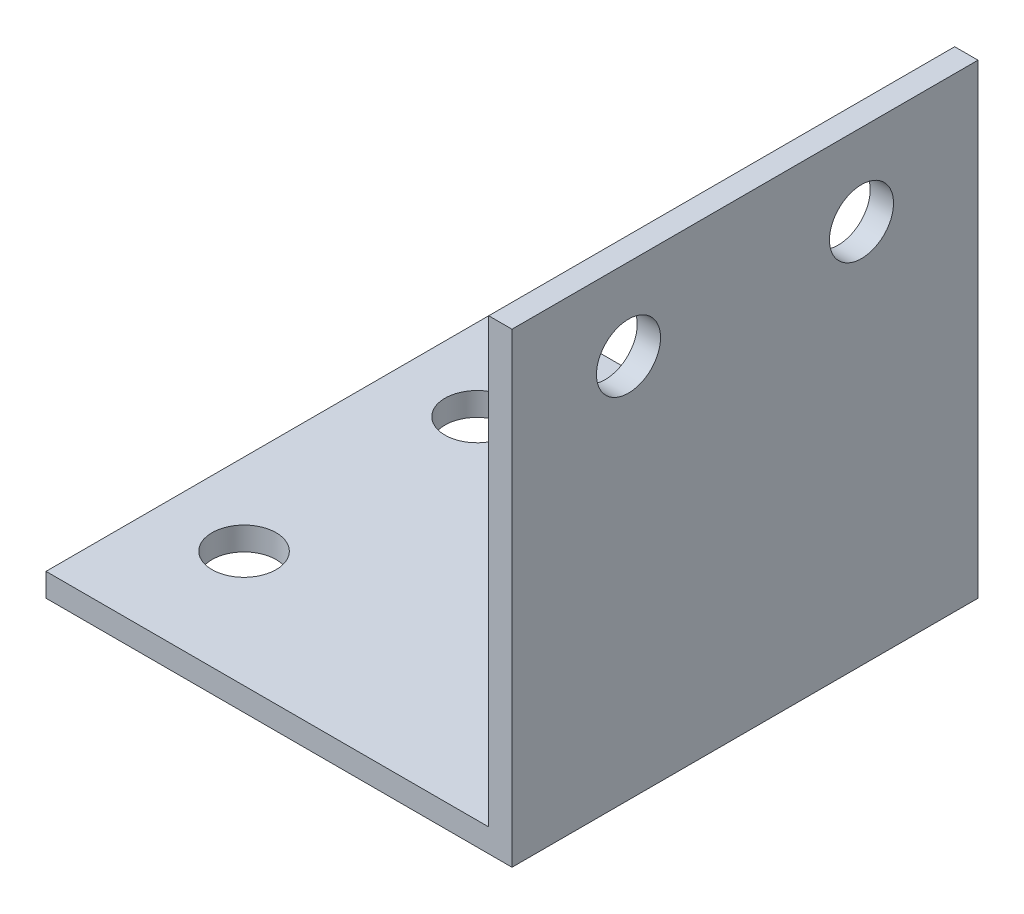
SolidWorks part; units mm, degrees
ref_plane "前视基准面" through (0, 0, 0) normal (0, 0, 1) x (1, 0, 0)
ref_plane "上视基准面" through (0, 0, 0) normal (0, 1, 0) x (1, 0, 0)
ref_plane "右视基准面" through (0, 0, 0) normal (1, 0, 0) x (0, 0, -1)
other "Configuration Table"
sketch "草图1" plane through (0, 0, 0) normal (0, 0, 1) x (1, 0, 0)
  line L0 (0, 0) -> (0, -2)
  line L1 (0, -2) -> (40, -2)
  line L2 (40, -2) -> (40, 38)
  line L3 (40, 38) -> (38, 38)
  line L4 (38, 38) -> (38, 0)
  line L5 (38, 0) -> (0, 0)
  dimension "D1" = 2
  dimension "D2" = 2
  dimension "D3" = 40
  dimension "D4" = 40
extrude "凸台-拉伸1" add sketch "草图1" along normal blind 40
sketch "草图2" plane through (40, 0, 0) normal (1, 0, 0) x (0, 0, -1)
  line L0 (-20, 38) -> (-20, -2) construction
  line L1 (-40, 38) -> (0, 38) construction
  line L2 (-40, -2) -> (0, -2) construction
  circle A0 centre (-30, 31) radius 2.75
  circle A1 centre (-10, 31) radius 2.75
  dimension "D1" = 5.5
  dimension "D3" = 7
  dimension "D2" = 20
extrude "切除-拉伸1" cut sketch "草图2" against normal blind 40
ref_plane "基准面1" through (19, 19, 0) normal (0.7071, 0.7071, 0) x (0, 0, -1)
mirror "镜向1" about plane through (19, 19, 0) normal (0.7071, 0.7071, 0) of "切除-拉伸1"
